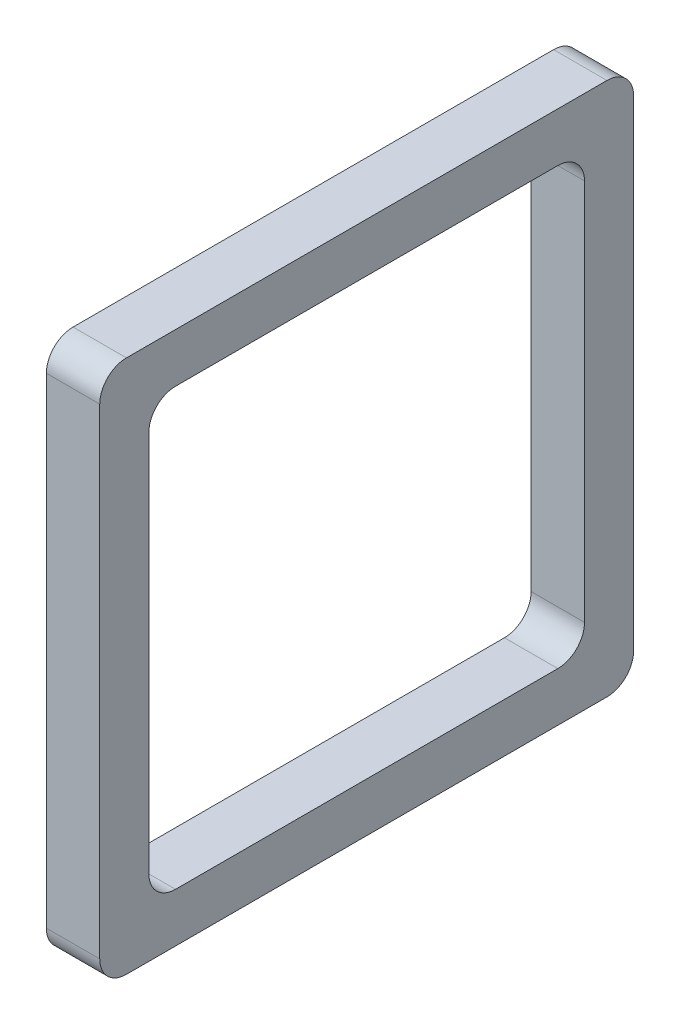
SolidWorks part; units mm, degrees
material "Nylon 101"
ref_plane "Front Plane" through (0, 0, 0) normal (0, 0, 1) x (1, 0, 0)
ref_plane "Top Plane" through (0, 0, 0) normal (0, 1, 0) x (1, 0, 0)
ref_plane "Right Plane" through (0, 0, 0) normal (1, 0, 0) x (0, 0, -1)
sketch "Sketch1" plane through (0, 0, 0) normal (1, 0, 0) x (0, 0, -1)
  line L0 (2.921, 2.921) -> (2.921, 28.829)
  line L1 (0, 0) -> (31.75, 0)
  line L2 (0, 0) -> (0, 31.75)
  line L3 (0, 31.75) -> (31.75, 31.75)
  line L4 (31.75, 0) -> (31.75, 31.75)
  line L5 (2.921, 28.829) -> (28.829, 28.829)
  line L6 (28.829, 2.921) -> (28.829, 28.829)
  line L7 (2.921, 2.921) -> (28.829, 2.921)
  dimension "D1" = 31.75
  dimension "D2" = 31.75
  dimension "D3" = 2.921
extrude "Boss-Extrude1" add sketch "Sketch1" along normal mid plane 3.175
fillet "Fillet1" radius 1.5875 8 edges at (0, 2.921, -28.829) (0, 28.829, -28.829) (0, 28.829, -2.921) (0, 2.921, -2.921) (0, 31.75, -31.75) (0, 0, -31.75) (0, 0, 0) (0, 31.75, 0)
